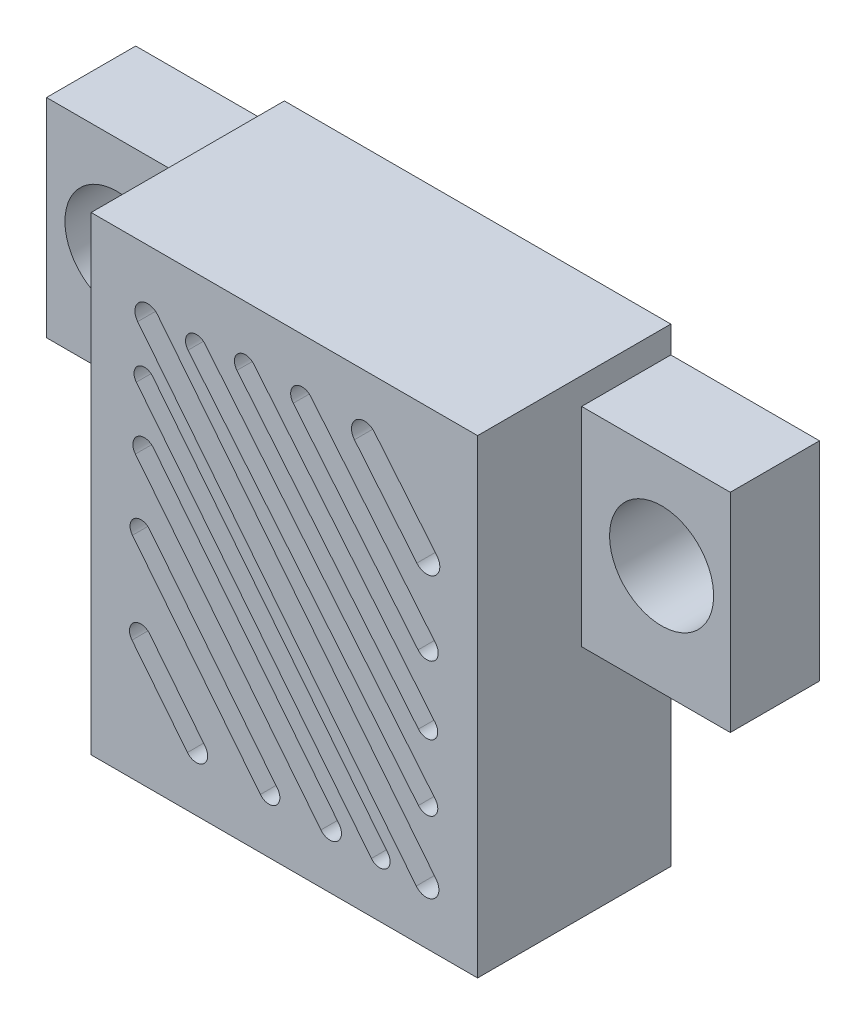
SolidWorks part; units mm, degrees
ref_plane "Front Plane" through (0, 0, 0) normal (0, 0, 1) x (1, 0, 0)
ref_plane "Top Plane" through (0, 0, 0) normal (0, 1, 0) x (1, 0, 0)
ref_plane "Right Plane" through (0, 0, 0) normal (1, 0, 0) x (0, 0, -1)
sketch "Sketch1" plane through (0, 0, 0) normal (0, 0, 1) x (1, 0, 0)
  line L1 (6.5, -7.9) -> (-6.5, -7.9)
  line L2 (6.5, -7.9) -> (6.5, 7.9)
  line L3 (6.5, 7.9) -> (-6.5, 7.9)
  line L4 (-6.5, -7.9) -> (-6.5, 7.9)
  line L5 (6.5, -7.9) -> (-6.5, 7.9) construction
  line L6 (6.5, 7.9) -> (-6.5, -7.9) construction
  point P0 (0, 0)
  dimension "D1" = 13
  dimension "D2" = 15.8
extrude "Boss-Extrude1" add sketch "Sketch1" along normal blind 6.5
shell "Shell1" thickness 1
sketch "Sketch2" plane through (0, 0, 5.5) normal (0, 0, -1) x (-1, 0, 0)
  line L0 (-5.5, -6.9) -> (5.5, 6.9) construction
  line L1 (-4.7708, -5.9852) -> (4.5993, 5.7701) construction
  line L2 (-5.1051, -5.7187) -> (4.2651, 6.0365)
  line L3 (-4.4365, -6.2516) -> (4.9336, 5.5036)
  line L4 (-3.2041, -5.9834) -> (4.704, 3.9377) construction
  line L5 (-3.4798, -5.7636) -> (4.4283, 4.1575)
  line L6 (-2.9284, -6.2031) -> (4.9797, 3.7179)
  line L7 (-1.5333, -5.9803) -> (4.7078, 1.8493) construction
  line L8 (-1.8362, -5.7389) -> (4.4048, 2.0908)
  line L9 (-1.2303, -6.2218) -> (5.0107, 1.6078)
  line L10 (0.5185, -5.9768) -> (4.8216, -0.5784) construction
  line L11 (0.2306, -5.7474) -> (4.5338, -0.3489)
  line L12 (0.8064, -6.2063) -> (5.1095, -0.8078)
  line L13 (2.9613, -5.9724) -> (4.8272, -3.6317) construction
  line L14 (2.6625, -5.7343) -> (4.5284, -3.3935)
  line L15 (3.2601, -6.2106) -> (5.126, -3.8698)
  line L16 (-4.7933, -3.635) -> (2.9571, 5.7523) construction
  line L17 (-5.0766, -3.4012) -> (2.6738, 5.9862)
  line L18 (-4.5101, -3.8689) -> (3.2404, 5.5185)
  line L19 (-4.7933, -1.4096) -> (1.3128, 5.9862) construction
  line L20 (-5.0759, -1.1763) -> (1.0303, 6.2195)
  line L21 (-4.5108, -1.6429) -> (1.5954, 5.7529)
  line L22 (-4.7933, 0.9009) -> (-0.5948, 5.9862) construction
  line L23 (-5.0884, 1.1445) -> (-0.8899, 6.2298)
  line L24 (-4.4983, 0.6573) -> (-0.2997, 5.7426)
  line L25 (-4.7933, 3.4435) -> (-2.6941, 5.9862) construction
  line L26 (-5.1294, 3.721) -> (-3.0302, 6.2637)
  line L27 (-4.4572, 3.166) -> (-2.358, 5.7087)
  arc A0 (-5.1051, -5.7187) -> (-4.4365, -6.2516) centre (-4.7708, -5.9852) ccw
  arc A1 (4.9336, 5.5036) -> (4.2651, 6.0365) centre (4.5993, 5.7701) ccw
  arc A2 (-3.4798, -5.7636) -> (-2.9284, -6.2031) centre (-3.2041, -5.9834) ccw
  arc A3 (4.9797, 3.7179) -> (4.4283, 4.1575) centre (4.704, 3.9377) ccw
  arc A4 (-1.8362, -5.7389) -> (-1.2303, -6.2218) centre (-1.5333, -5.9803) ccw
  arc A5 (5.0107, 1.6078) -> (4.4048, 2.0908) centre (4.7078, 1.8493) ccw
  arc A6 (0.2306, -5.7474) -> (0.8064, -6.2063) centre (0.5185, -5.9768) ccw
  arc A7 (5.1095, -0.8078) -> (4.5338, -0.3489) centre (4.8216, -0.5784) ccw
  arc A8 (2.6625, -5.7343) -> (3.2601, -6.2106) centre (2.9613, -5.9724) ccw
  arc A9 (5.126, -3.8698) -> (4.5284, -3.3935) centre (4.8272, -3.6317) ccw
  arc A10 (-5.0766, -3.4012) -> (-4.5101, -3.8689) centre (-4.7933, -3.635) ccw
  arc A11 (3.2404, 5.5185) -> (2.6738, 5.9862) centre (2.9571, 5.7523) ccw
  arc A12 (-5.0759, -1.1763) -> (-4.5108, -1.6429) centre (-4.7933, -1.4096) ccw
  arc A13 (1.5954, 5.7529) -> (1.0303, 6.2195) centre (1.3128, 5.9862) ccw
  arc A14 (-5.0884, 1.1445) -> (-4.4983, 0.6573) centre (-4.7933, 0.9009) ccw
  arc A15 (-0.2997, 5.7426) -> (-0.8899, 6.2298) centre (-0.5948, 5.9862) ccw
  arc A16 (-5.1294, 3.721) -> (-4.4572, 3.166) centre (-4.7933, 3.4435) ccw
  arc A17 (-2.358, 5.7087) -> (-3.0302, 6.2637) centre (-2.6941, 5.9862) ccw
  point P6 (-0.0857, -0.1076)
  point P11 (0.75, -1.0228)
  point P18 (1.5873, -2.0655)
  point P25 (2.6701, -3.2776)
  point P32 (3.8942, -4.802)
  point P41 (-0.9181, 1.0587)
  point P46 (-1.7403, 2.2883)
  point P53 (-2.6941, 3.4435)
  point P60 (-3.7437, 4.7149)
extrude "Cut-Extrude2" cut sketch "Sketch2" against normal blind 2.5
sketch "Sketch3" plane through (0, 0, 0) normal (0, 0, -1) x (-1, 0, 0)
  line L0 (6.5, 7.9) -> (6.5, -7.9) construction
  line L1 (6.5, 0) -> (11.5, 0)
  line L2 (6.5, 0) -> (6.5, 7)
  line L3 (6.5, 7) -> (11.5, 7)
  line L4 (11.5, 0) -> (11.5, 7)
  line L5 (-6.5, -7.9) -> (-6.5, 7.9) construction
  line L6 (-6.5, 0) -> (-11.5, 0)
  line L7 (-6.5, 0) -> (-6.5, 7)
  line L8 (-6.5, 7) -> (-11.5, 7)
  line L9 (-11.5, 0) -> (-11.5, 7)
  dimension "D1" = 5
  dimension "D2" = 7
  dimension "D3" = 7
  dimension "D4" = 5
extrude "Boss-Extrude2" add sketch "Sketch3" against normal blind 3
sketch "Sketch4" plane through (0, 0, 0) normal (0, 0, -1) x (-1, 0, 0)
  circle A0 centre (-9.1892, 3.7021) radius 1.75
  circle A1 centre (9.1309, 3.7021) radius 1.75
  dimension "D1" = 3.5
  dimension "D2" = 3.5
extrude "Cut-Extrude3" cut sketch "Sketch4" against normal blind 5
